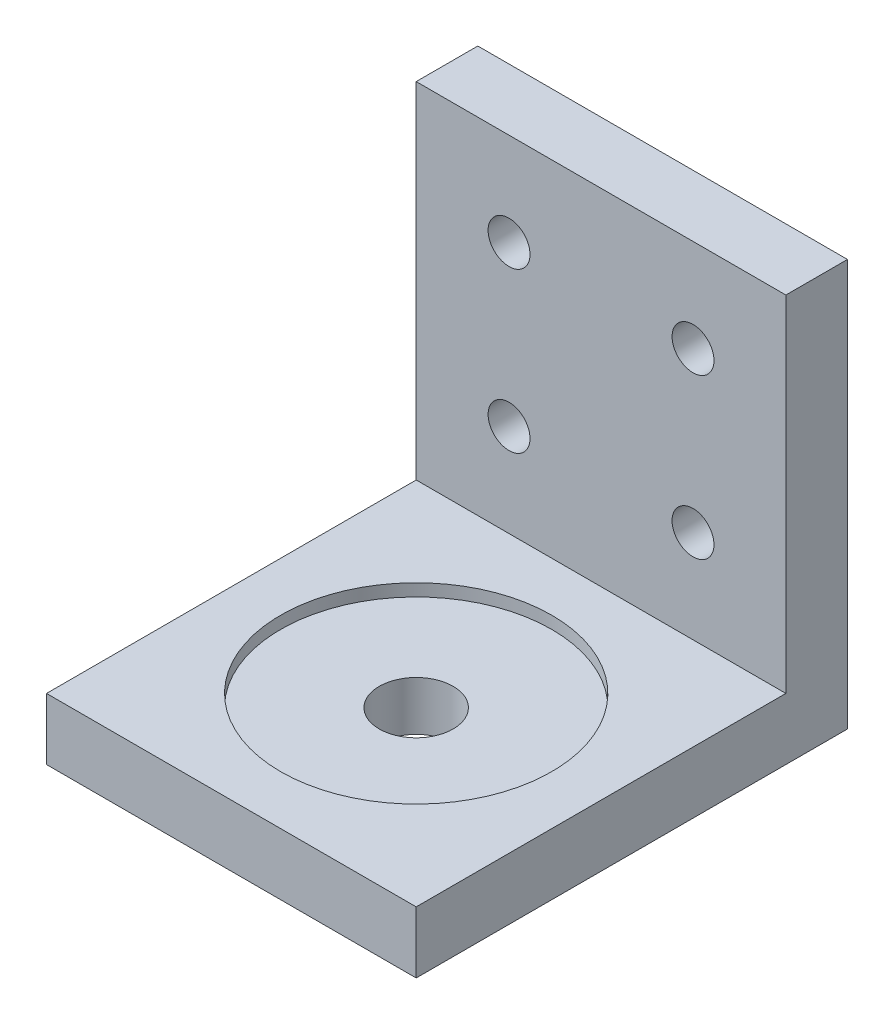
SolidWorks part; units mm, degrees
material "PVC 0.007 Plasticized"
ref_plane "Front Plane" through (0, 0, 0) normal (0, 0, 1) x (1, 0, 0)
ref_plane "Top Plane" through (0, 0, 0) normal (0, 1, 0) x (1, 0, 0)
ref_plane "Right Plane" through (0, 0, 0) normal (1, 0, 0) x (0, 0, -1)
sketch "Sketch1" plane through (0, 0, 0) normal (0, 1, 0) x (1, 0, 0)
  line L1 (15, -18.665) -> (-15, -18.665)
  line L2 (15, -18.665) -> (15, 11.335)
  line L3 (15, 11.335) -> (-15, 11.335)
  line L4 (-15, -18.665) -> (-15, 11.335)
  line L5 (15, -18.665) -> (-15, 11.335) construction
  line L6 (15, 11.335) -> (-15, -18.665) construction
  point P0 (0, 0)
  point P5 (15, -18.665)
  dimension "D1" = 30
  dimension "D2" = 30
extrude "Boss-Extrude1" add sketch "Sketch1" along normal blind 5
sketch "Sketch2" plane through (0, 5, 0) normal (0, 1, 0) x (1, 0, 0)
  circle A0 centre (0, -3.665) radius 11
  dimension "D1" = 22
extrude "Cut-Extrude1" cut sketch "Sketch2" against normal blind 1
sketch "Sketch5" plane through (0, 0, 0) normal (0, 1, 0) x (1, 0, 0)
  line L0 (-15, 11.335) -> (-15, 16.335)
  line L1 (15, 11.335) -> (15, 16.335)
  line L2 (15, 16.335) -> (-15, 16.335)
  line L3 (-15, 11.335) -> (15, 11.335)
  dimension "D1" = 5
extrude "Boss-Extrude3" add sketch "Sketch5" along normal blind 33
sketch "Sketch6" plane through (0, 0, -11.335) normal (0, 0, 1) x (1, 0, 0)
  line L0 (0, 33) -> (0, 0) construction
  line L1 (15, 19) -> (-15, 19) construction
  circle A0 centre (-7.4644, 12.5325) radius 1.7
  circle A1 centre (7.4644, 12.5325) radius 1.7
  circle A2 centre (7.4644, 25.4675) radius 1.7
  circle A3 centre (-7.4644, 25.4675) radius 1.7
  dimension "D1" = 3.4
extrude "Cut-Extrude2" cut sketch "Sketch6" against normal blind 9.378
sketch "Sketch7" plane through (0, 4, 0) normal (0, 1, 0) x (1, 0, 0)
  circle A0 centre (0, -3.665) radius 3
  dimension "D1" = 6
extrude "Cut-Extrude3" cut sketch "Sketch7" against normal blind 9.378
